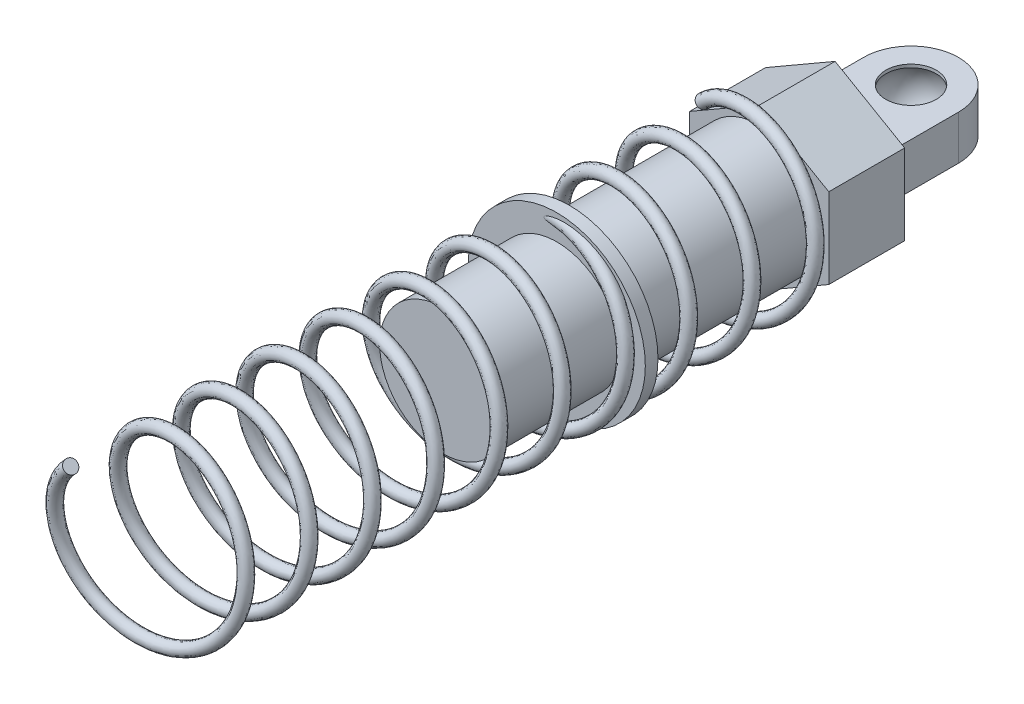
SolidWorks part; units mm, degrees
ref_plane "前视基准面" through (0, 0, 0) normal (0, 0, 1) x (1, 0, 0)
ref_plane "上视基准面" through (0, 0, 0) normal (0, 1, 0) x (1, 0, 0)
ref_plane "右视基准面" through (0, 0, 0) normal (1, 0, 0) x (0, 0, -1)
sketch "草图1" plane through (0, 0, 0) normal (0, 0, 1) x (1, 0, 0)
  line L1 (0, 12.7017) -> (-11, 6.3509)
  line L2 (-11, 6.3509) -> (-11, -6.3509)
  line L3 (-11, -6.3509) -> (0, -12.7017)
  line L4 (0, -12.7017) -> (11, -6.3509)
  line L5 (11, -6.3509) -> (11, 6.3509)
  line L6 (11, 6.3509) -> (0, 12.7017)
  circle A0 centre (0, 0) radius 11 construction
  dimension "D1" = 22
extrude "凸台-拉伸1" add sketch "草图1" along normal blind 12
sketch "草图2" plane through (0, 0, 12) normal (0, 0, 1) x (1, 0, 0)
  circle A0 centre (0, 0) radius 10
  dimension "D1" = 20
extrude "凸台-拉伸2" add sketch "草图2" along normal blind 50
ref_plane "基准面1" through (0, 0, 42) normal (0, 0, 1) x (1, 0, 0)
sketch "草图4" plane through (0, 0, 42) normal (0, 0, 1) x (1, 0, 0)
  circle A0 centre (0, 0) radius 14
  dimension "D1" = 28
extrude "凸台-拉伸3" add sketch "草图4" along normal blind 2
sketch "草图5" plane through (0, 0, 0) normal (0, 1, 0) x (1, 0, 0)
  line L0 (-7.5, 12) -> (-7.5, 0)
  line L1 (0, 0) -> (-11, 0) construction
  line L2 (-7.5, 0) -> (7.5, 0)
  line L3 (11, 0) -> (0, 0) construction
  line L4 (7.5, 0) -> (7.5, 12)
  circle A0 centre (0, 12) radius 7.5
  dimension "D2" = 15
  dimension "D1" = 12
extrude "凸台-拉伸4" add sketch "草图5" along normal mid plane 7 contours A0 | A0 L0 L2 L4
sketch "草图6" plane through (0, 3.5, 0) normal (0, 1, 0) x (1, 0, 0)
  circle A0 centre (0, 12) radius 4
  dimension "D1" = 8
extrude "切除-拉伸1" cut sketch "草图6" against normal blind 7
sketch "草图7" plane through (0, 0, 0) normal (0, 1, 0) x (1, 0, 0)
  line L0 (0, 15.9375) -> (0, 6.4292) construction
  line L1 (0, 17) -> (0, 7)
  arc A0 (0, 7) -> (0, 17) centre (0, 12) ccw
  dimension "D1" = 10
revolve "切除-旋转1" cut sketch "草图7" angle 360 about L0
sketch "草图8" plane through (0, 0, 12) normal (0, 0, 1) x (1, 0, 0)
  circle A0 centre (0, 0) radius 12.5
  dimension "D1" = 25
curve "螺旋线/涡状线1" pitch 10 height 100 turns 10
sweep "扫描1" add path "螺旋线/涡状线1" circular profile diameter 2 parameters "D3"=2
